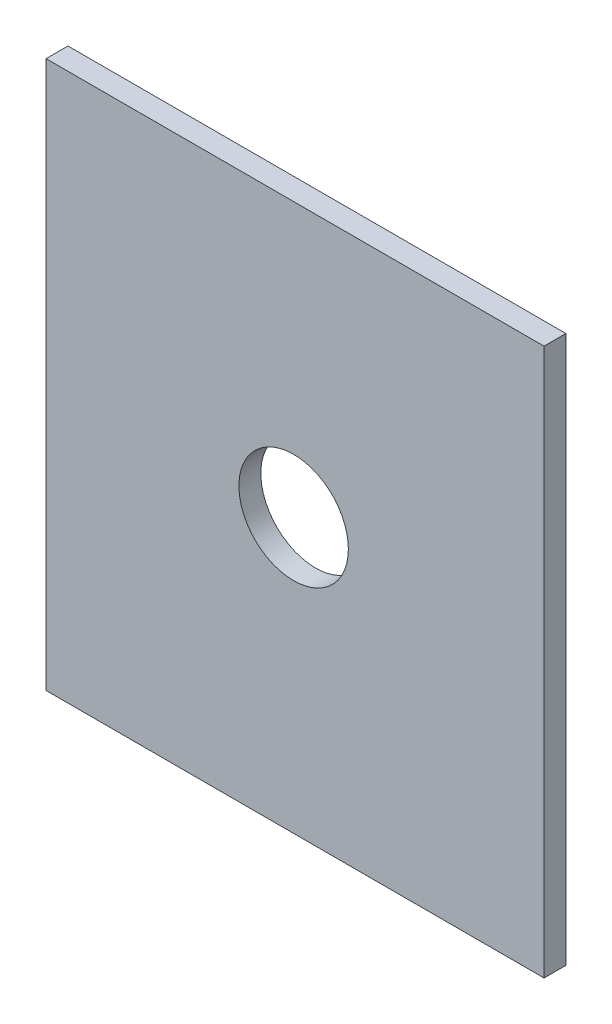
SolidWorks part; units mm, degrees
ref_plane "Front Plane" through (0, 0, 0) normal (0, 0, 1) x (1, 0, 0)
ref_plane "Top Plane" through (0, 0, 0) normal (0, 1, 0) x (1, 0, 0)
ref_plane "Right Plane" through (0, 0, 0) normal (1, 0, 0) x (0, 0, -1)
sketch "Sketch1" plane through (0, 0, 0) normal (0, 0, 1) x (1, 0, 0)
  line L1 (-56, -50) -> (35, -50)
  line L2 (-56, -50) -> (-56, 50)
  line L3 (-56, 50) -> (35, 50)
  line L4 (35, -50) -> (35, 50)
  circle A0 centre (-10.76, 0) radius 10
  point P0 (0, 0)
  dimension "D3" = 20
  dimension "D1" = 56
  dimension "D2" = 100
  dimension "D4" = 10.76
  dimension "D5" = 35
extrude "Boss-Extrude1" add sketch "Sketch1" along normal blind 4
